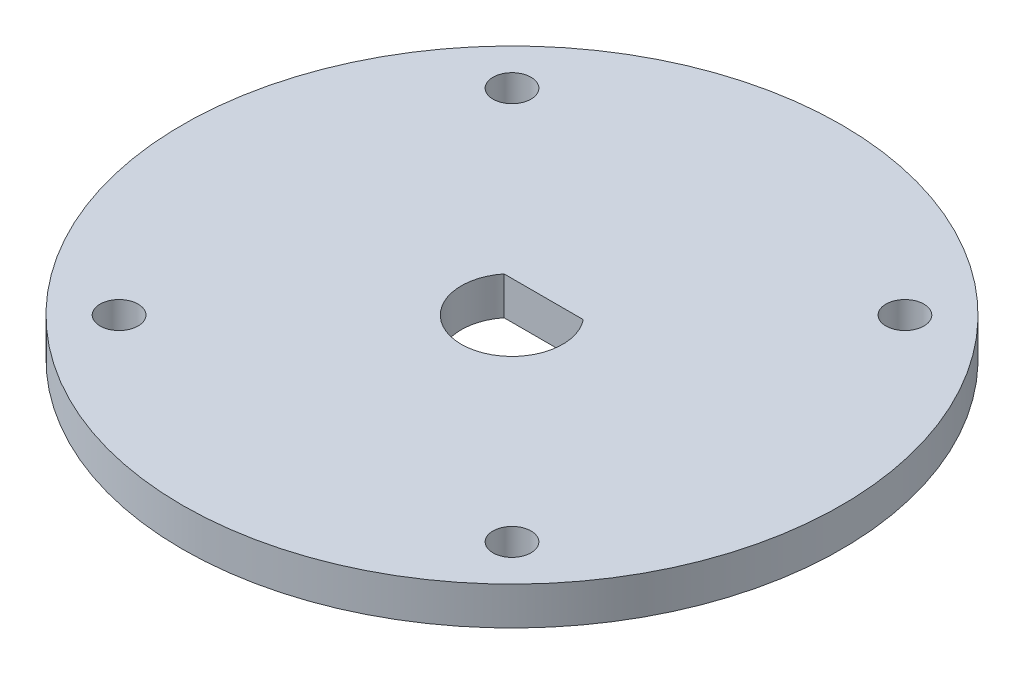
SolidWorks part; units mm, degrees
ref_plane "Спереди" through (0, 0, 0) normal (0, 0, 1) x (1, 0, 0)
ref_plane "Сверху" through (0, 0, 0) normal (0, 1, 0) x (1, 0, 0)
ref_plane "Справа" through (0, 0, 0) normal (1, 0, 0) x (0, 0, -1)
sketch "Эскиз1" plane through (0, 0, 0) normal (0, 1, 0) x (1, 0, 0)
  line L0 (-58.4522, 31.2788) -> (-27.4522, 31.2788) construction
  line L5 (-27.4522, 31.2788) -> (-27.4522, 0.2788) construction
  line L6 (-27.4522, 0.2788) -> (-58.4522, 0.2788) construction
  line L7 (-58.4522, 0.2788) -> (-58.4522, 31.2788) construction
  line L8 (-42.9522, 36.7788) -> (-42.9522, -5.2212) construction
  line L9 (-42.9522, -5.2212) -> (-21.9522, 15.7788) construction
  line L10 (-21.9522, 15.7788) -> (-63.9522, 15.7788) construction
  line L11 (-46.0747, 18.2788) -> (-39.8297, 18.2788)
  circle A0 centre (-58.4522, 31.2788) radius 1.5
  circle A1 centre (-58.4522, 0.2788) radius 1.5
  circle A2 centre (-27.4522, 31.2788) radius 1.5
  circle A3 centre (-27.4522, 0.2788) radius 1.5
  arc A4 (-46.0747, 18.2788) -> (-39.8297, 18.2788) centre (-42.9522, 15.7788) ccw
  circle A5 centre (-42.9522, 15.7788) radius 26
  dimension "D8" = 3
  dimension "D9" = 3
  dimension "D10" = 3
  dimension "D11" = 8
  dimension "D2" = 52
  dimension "D3" = 31
  dimension "D4" = 31
  dimension "D5" = 15.5
  dimension "D6" = 15.5
  dimension "D12" = 2.5
extrude "Бобышка-Вытянуть1" add sketch "Эскиз1" along normal blind 3
